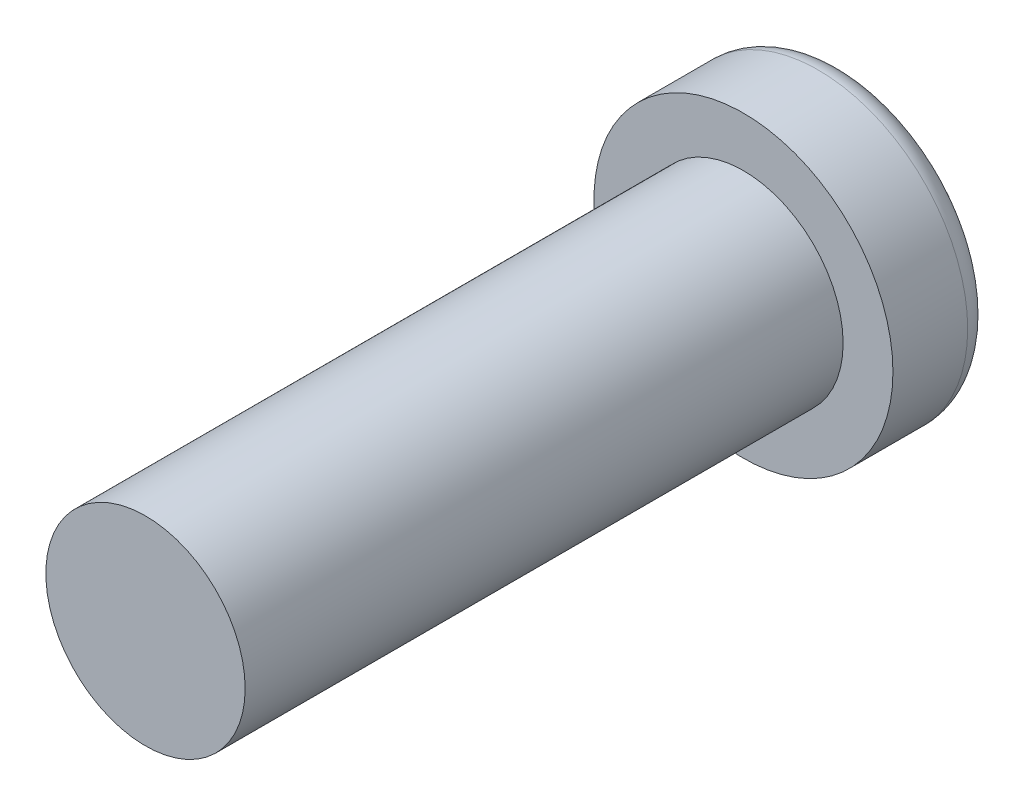
SolidWorks part; units mm, degrees
ref_plane "Front Plane" through (0, 0, 0) normal (0, 0, 1) x (1, 0, 0)
ref_plane "Top Plane" through (0, 0, 0) normal (0, 1, 0) x (1, 0, 0)
ref_plane "Right Plane" through (0, 0, 0) normal (1, 0, 0) x (0, 0, -1)
sketch "Sketch1" plane through (0, 0, 0) normal (0, 0, 1) x (1, 0, 0)
  circle A0 centre (0, 0) radius 3
  dimension "D1" = 6
extrude "Boss-Extrude1" add sketch "Sketch1" along normal blind 2
sketch "Sketch2" plane through (0, 0, 2) normal (0, 0, 1) x (1, 0, 0)
  circle A0 centre (0, 0) radius 2
  dimension "D1" = 4
extrude "Boss-Extrude2" add sketch "Sketch2" along normal blind 12
fillet "Fillet2" radius 0.5 1 edges at (3, 0, 0)
